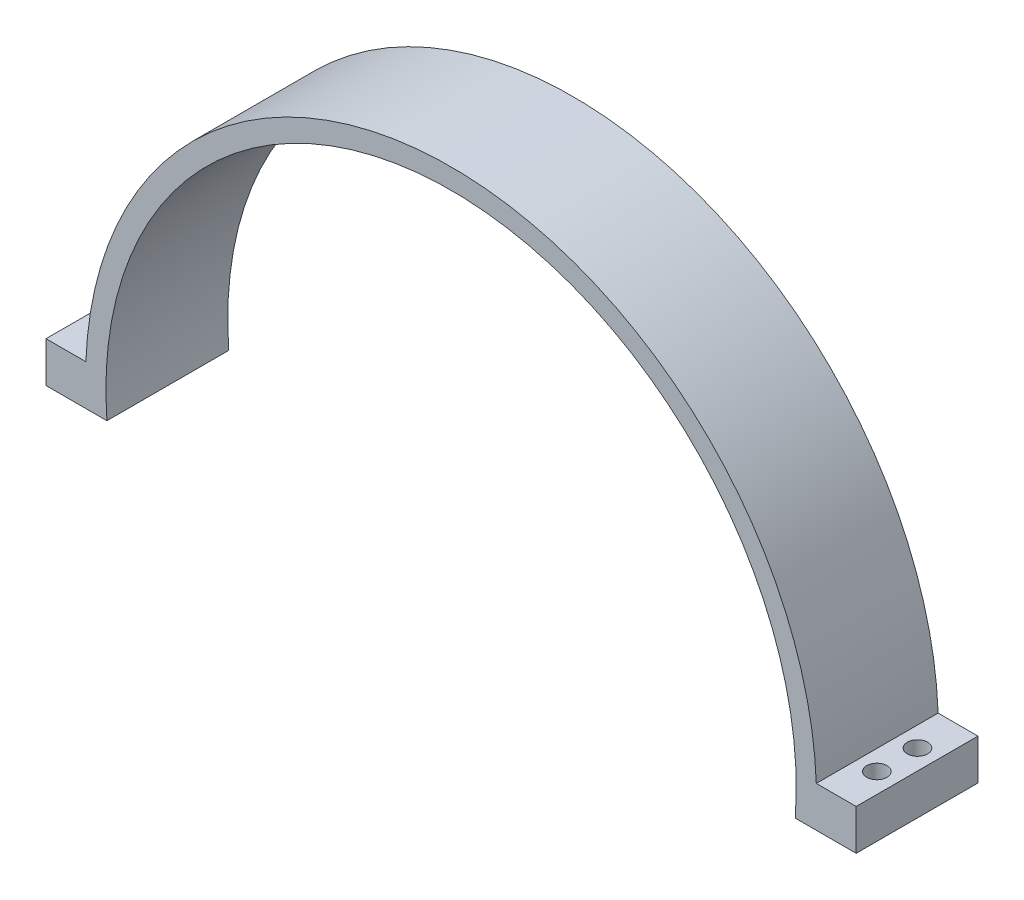
SolidWorks part; units mm, degrees
ref_plane "Ön Düzlem" through (0, 0, 0) normal (0, 0, 1) x (1, 0, 0)
ref_plane "Üst Düzlem" through (0, 0, 0) normal (0, 1, 0) x (1, 0, 0)
ref_plane "Sağ Düzlem" through (0, 0, 0) normal (1, 0, 0) x (0, 0, -1)
sketch "Sketch1" plane through (0, 0, 0) normal (0, 0, 1) x (1, 0, 0)
  line L0 (0, 85) -> (0, 0) construction
  line L5 (89.9329, 3.4747) -> (99.7492, 3.4747)
  line L6 (99.7492, 3.4747) -> (99.7492, -6.5253)
  line L7 (99.7492, -6.5253) -> (84.7492, -6.5253)
  line L9 (-89.9329, 3.4747) -> (-99.7492, 3.4747)
  line L10 (-99.7492, 3.4747) -> (-99.7492, -6.5253)
  line L11 (-99.7492, -6.5253) -> (-84.7492, -6.5253)
  arc A2 (84.7492, -6.5253) -> (-84.7492, -6.5253) centre (0, 0) ccw
  arc A4 (89.9329, 3.4747) -> (-89.9329, 3.4747) centre (0, 0) ccw
  dimension "D1" = 15
  dimension "D2" = 85
  dimension "D3" = 90
  dimension "D5" = 10
extrude "Boss-Extrude1" add sketch "Sketch1" along normal blind 30
sketch "Sketch2" plane through (0, 3.4747, 0) normal (0, 1, 0) x (1, 0, 0)
  line L0 (0, 0) -> (0, -30) construction
  line L1 (89.9329, 0) -> (-89.9329, 0) construction
  line L2 (-89.9329, -30) -> (89.9329, -30) construction
  line L3 (-94.841, 0) -> (-94.841, -30) construction
  line L4 (-89.9329, 0) -> (-99.7492, 0) construction
  line L5 (-89.9329, -30) -> (-99.7492, -30) construction
  circle A0 centre (-94.841, -10) radius 2.5
  circle A1 centre (-94.841, -20) radius 2.5
  circle A2 centre (94.841, -20) radius 2.5
  circle A3 centre (94.841, -10) radius 2.5
  dimension "D2" = 5
  dimension "D3" = 5
  dimension "D1" = 10
  dimension "D4" = 10
extrude "Cut-Extrude1" cut sketch "Sketch2" against normal blind 30
